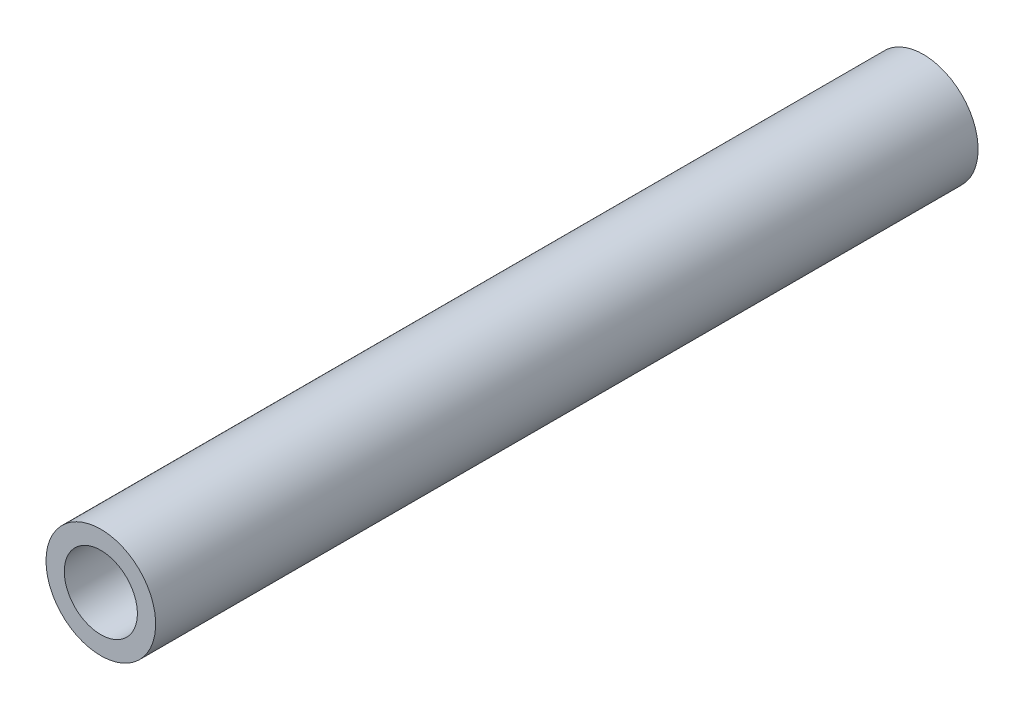
SolidWorks part; units mm, degrees
material "C-Fibra di vetro"
ref_plane "Piano frontale" through (0, 0, 0) normal (0, 0, 1) x (1, 0, 0)
ref_plane "Piano superiore" through (0, 0, 0) normal (0, 1, 0) x (1, 0, 0)
ref_plane "Piano destro" through (0, 0, 0) normal (1, 0, 0) x (0, 0, -1)
sketch "Schizzo1" plane through (0, 0, 0) normal (0, 0, 1) x (1, 0, 0)
  circle A0 centre (75, -87.5) radius 3
  circle A1 centre (75, -87.5) radius 2
  dimension "D1" = 6
  dimension "D2" = 1
extrude "Estrusione-Estrusione1" add sketch "Schizzo1" along normal up to surface (45 mm away)
